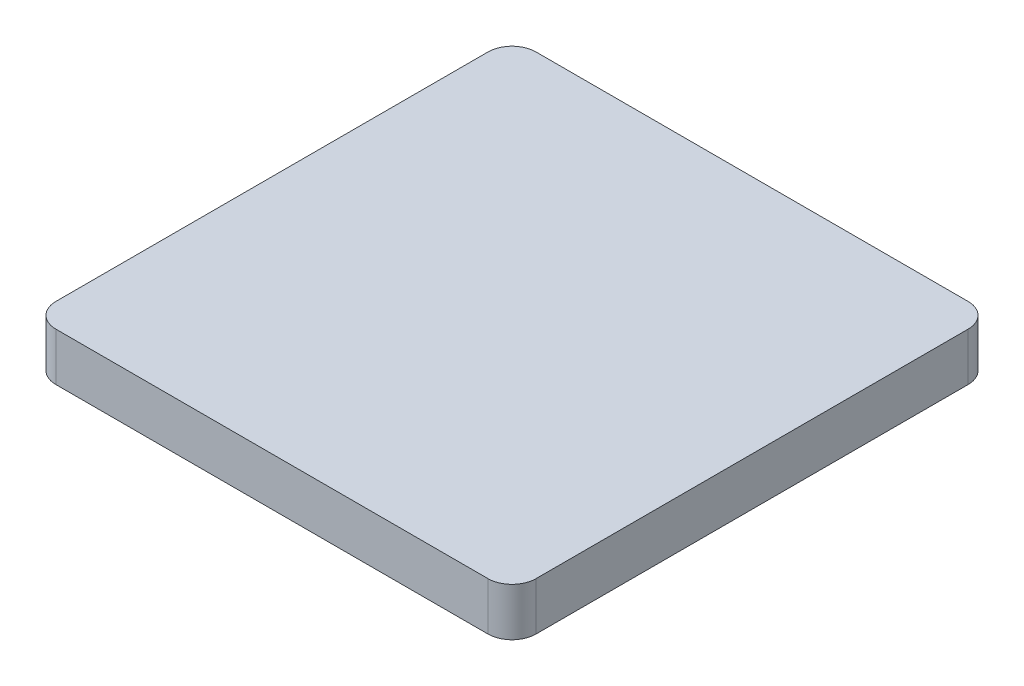
SolidWorks part; units mm, degrees
ref_plane "Front Plane" through (0, 0, 0) normal (0, 0, 1) x (1, 0, 0)
ref_plane "Top Plane" through (0, 0, 0) normal (0, 1, 0) x (1, 0, 0)
ref_plane "Right Plane" through (0, 0, 0) normal (1, 0, 0) x (0, 0, -1)
sketch "Sketch1" plane through (0, 0, 0) normal (0, 1, 0) x (1, 0, 0)
  line L1 (-28.575, -31.75) -> (28.575, -31.75)
  line L2 (-31.75, -28.575) -> (-31.75, 28.575)
  line L3 (-28.575, 31.75) -> (28.575, 31.75)
  line L4 (31.75, -28.575) -> (31.75, 28.575)
  line L5 (-31.75, -31.75) -> (31.75, 31.75) construction
  line L6 (-31.75, 31.75) -> (31.75, -31.75) construction
  arc A0 (-31.75, 28.575) -> (-28.575, 31.75) centre (-28.575, 28.575) cw
  arc A1 (-28.575, -31.75) -> (-31.75, -28.575) centre (-28.575, -28.575) cw
  arc A2 (28.575, -31.75) -> (31.75, -28.575) centre (28.575, -28.575) ccw
  arc A3 (28.575, 31.75) -> (31.75, 28.575) centre (28.575, 28.575) cw
  point P0 (0, 0)
  dimension "D2" = 3.175
  dimension "D1" = 63.5
extrude "Boss-Extrude1" add sketch "Sketch1" along normal blind 6.35
